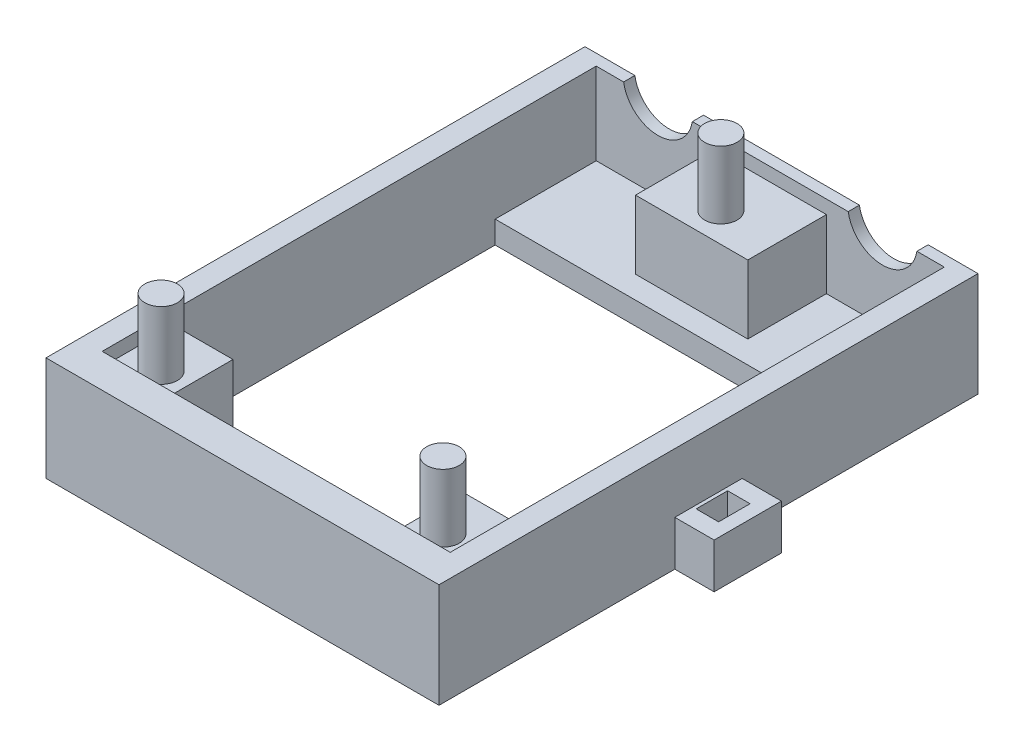
SolidWorks part; units mm, degrees
ref_plane "Front Plane" through (0, 0, 0) normal (0, 0, 1) x (1, 0, 0)
ref_plane "Top Plane" through (0, 0, 0) normal (0, 1, 0) x (1, 0, 0)
ref_plane "Right Plane" through (0, 0, 0) normal (1, 0, 0) x (0, 0, -1)
sketch "Sketch1" plane through (0, 0, 0) normal (0, 1, 0) x (1, 0, 0)
  line L1 (-17.5, 24) -> (17.5, 24)
  line L2 (-17.5, 24) -> (-17.5, -24)
  line L3 (-17.5, -24) -> (17.5, -24)
  line L4 (17.5, 24) -> (17.5, -24)
  line L5 (-44.2539, 0) -> (44.2539, 0) construction
  line L6 (0, -44.7868) -> (0, 44.7868) construction
  dimension "D2" = 35
  dimension "D1" = 48
  dimension "D3" = 24
  dimension "D4" = 17.5
extrude "Boss-Extrude1" add sketch "Sketch1" along normal blind 2
sketch "Sketch2" plane through (0, 2, 0) normal (0, 1, 0) x (1, 0, 0)
  line L1 (-15.5, 23) -> (15.5, 23)
  line L2 (-15.5, 23) -> (-15.5, -21)
  line L3 (-15.5, -21) -> (15.5, -21)
  line L4 (15.5, 23) -> (15.5, -21)
  line L6 (17.5, -24) -> (17.5, 24) construction
  line L7 (-17.5, -24) -> (17.5, -24) construction
  line M5 (-17.5, 24) -> (-17.5, -24)
  line M6 (-17.5, -24) -> (17.5, -24)
  line M7 (17.5, -24) -> (17.5, 24)
  line M8 (17.5, 24) -> (-17.5, 24)
  dimension "D1" = 2
  dimension "D2" = 3
  dimension "D3" = 31
  dimension "D4" = 44
extrude "Boss-Extrude2" add sketch "Sketch2" along normal blind 7.3 contours L1 L4 L3 L2 M8 M5 M6 M7
sketch "Sketch3" plane through (0, 2, 0) normal (0, 1, 0) x (1, 0, 0)
  line L0 (-15.5, 23) -> (15.5, 23) construction
  line L1 (-5, 23) -> (5, 23)
  line L2 (-5, 23) -> (-5, 16)
  line L3 (-5, 16) -> (5, 16)
  line L4 (5, 23) -> (5, 16)
  line L5 (15.5, 23) -> (15.5, -21) construction
  line L7 (-15.5, -21) -> (-10.25, -21)
  line L8 (-15.5, -21) -> (-15.5, -14.6)
  line L9 (-15.5, -14.6) -> (-10.25, -14.6)
  line L10 (-10.25, -21) -> (-10.25, -14.6)
  line L11 (15.5, -21) -> (10.25, -21)
  line L12 (15.5, -21) -> (15.5, -14.6)
  line L13 (15.5, -14.6) -> (10.25, -14.6)
  line L14 (10.25, -21) -> (10.25, -14.6)
  dimension "D1" = 10
  dimension "D2" = 7
  dimension "D3" = 10.5
  dimension "D4" = 5.25
  dimension "D5" = 5.25
  dimension "D6" = 6.4
  dimension "D7" = 6.4
extrude "Boss-Extrude3" add sketch "Sketch3" along normal blind 6.1
sketch "Sketch6" plane through (0, 0, -24) normal (0, 0, -1) x (-1, 0, 0)
  line L1 (-17.5, 9.3) -> (17.5, 9.3) construction
  line L2 (-17.5, 9.3) -> (-17.5, 0) construction
  arc A0 (-6.9406, 9.3) -> (-13.0594, 9.3) centre (-10, 9.8) cw
  arc A1 (13.0594, 9.3) -> (6.9406, 9.3) centre (10, 9.8) cw
  line M3 (17.5, 9.3) -> (-17.5, 9.3)
  dimension "D1" = 7.5
  dimension "D3" = 0.5
  dimension "D4" = 0.5
  dimension "D5" = 3.1
  dimension "D6" = 3.1
  dimension "D2" = 20
sketch "Sketch8" plane through (0, 0, 0) normal (0, 1, 0) x (1, 0, 0)
  line L0 (0, -44.7868) -> (0, 44.7868) construction
  line L2 (17.5, 24) -> (-17.5, 24) construction
  circle A0 centre (-12.55, -18.7) radius 1.45
  circle A1 centre (12.55, -18.7) radius 1.45
  circle A2 centre (0, 18.6) radius 1.45
  point P8 (0, 0)
  dimension "D1" = 2.9
  dimension "D7" = 2.9
  dimension "D8" = 2.9
  dimension "D3" = 25.1
  dimension "D5" = 12.55
  dimension "D6" = 5.4
  dimension "D2" = 37.3
  dimension "D4" = 37.3
sketch "Sketch9" plane through (0, 0, 0) normal (0, 1, 0) x (1, 0, 0)
  line L0 (-35.1135, -20.6) -> (29.9959, -20.6) construction
  line L1 (-15.5, 23) -> (15.5, 23) construction
  line L2 (-35.1135, 21.9) -> (32.5575, 21.9) construction
  point P4 (0, 23)
  dimension "D1" = 43.6
  dimension "D2" = 42.5
extrude "Cut-Extrude5" cut sketch "Sketch6" against normal blind 1 contours A0 M3 | A1 M3
sketch "Sketch10" plane through (0, 2, 0) normal (0, 1, 0) x (1, 0, 0)
  line L0 (-15.5, -14.6) -> (15.5, -14.6)
  line L1 (-15.5, 23) -> (-15.5, -14.6) construction
  line L2 (15.5, 23) -> (15.5, -21) construction
  line L4 (-15.5, 14) -> (15.5, 14)
  line L5 (15.5, 23) -> (15.5, -14.6) construction
  line L6 (-35.1135, 21.9) -> (32.5575, 21.9) construction
  line M5 (15.5, -14.6) -> (15.5, 23)
  line M11 (-15.5, 23) -> (-15.5, -14.6)
  dimension "D1" = 28.6
  dimension "D2" = 7.9
extrude "Cut-Extrude6" cut sketch "Sketch10" against normal through all contours L4 L0 M11 M5
extrude "Boss-Extrude4" add sketch "Sketch8" along normal blind 6 from surface at 8.1 starting at face at (0, 8.1, -19.5)
sketch "Sketch12" plane through (-17.5, 0, 0) normal (-1, 0, 0) x (0, 0, 1)
  line L0 (0, -44.2539) -> (0, 44.2539) construction
  line L1 (-3, 4) -> (3, 4)
  line L2 (-3, 4) -> (-3, 0)
  line L3 (-3, 0) -> (3, 0)
  line L4 (3, 4) -> (3, 0)
  line L6 (55, 0) -> (-55, 0) construction
  dimension "D1" = 6
  dimension "D2" = 4
  dimension "D3" = 3
extrude "Boss-Extrude5" add sketch "Sketch12" along normal blind 3.5
sketch "Sketch13" plane through (0, 4, 0) normal (0, 1, 0) x (1, 0, 0)
  line L0 (-44.2539, 0) -> (44.2539, 0) construction
  line L1 (-17.8, 1.4) -> (-19.8, 1.4)
  line L2 (-17.8, 1.4) -> (-17.8, -1.4)
  line L3 (-17.8, -1.4) -> (-19.8, -1.4)
  line L4 (-19.8, 1.4) -> (-19.8, -1.4)
  line L6 (-21, -3) -> (-21, 3) construction
  dimension "D1" = 2
  dimension "D2" = 2.8
  dimension "D3" = 1.4
  dimension "D4" = 1.2
extrude "Cut-Extrude7" cut sketch "Sketch13" against normal up to surface (4 mm away) up to face at (-9.625, 0, 0)
mirror "Mirror1" about plane through (0, 0, 0) normal (1, 0, 0) of "Boss-Extrude5", "Cut-Extrude7"
equation "\"fWidth\"=35"
equation "\"D2@Sketch1\"=\"fWidth\""
equation "\"fLength\"= 48"
equation "\"D1@Sketch1\"=\"fLength\""
equation "\"D3@Sketch1\"=\"fLength\"/2"
equation "\"D4@Sketch1\"=\"fWidth\"/2"
equation "\"wThickness\"=2"
equation "\"D1@Sketch2\"=\"wThickness\""
equation "\"D3@Sketch2\"=\"fWidth\"- 2* \"wThickness\""
equation "\"D4@Sketch2\"=\"fLength\"- 2 *\"wThickness\""
equation "\"wHeight\"= 7.3"
equation "\"D1@Boss-Extrude2\"=\"wHeight\""
equation "\"D3@Sketch3\"=(\"fWidth\"- 2 *\"wThickness\" - 10)/2"
equation "\"D1@Boss-Extrude3\"=\"wHeight\""
equation "\"holeDiam\"= 2.9"
equation "\"D8@Sketch8\"=\"holeDiam\""
equation "\"D1@Sketch8\"=\"holeDiam\""
equation "\"D7@Sketch8\"=\"holeDiam\""
